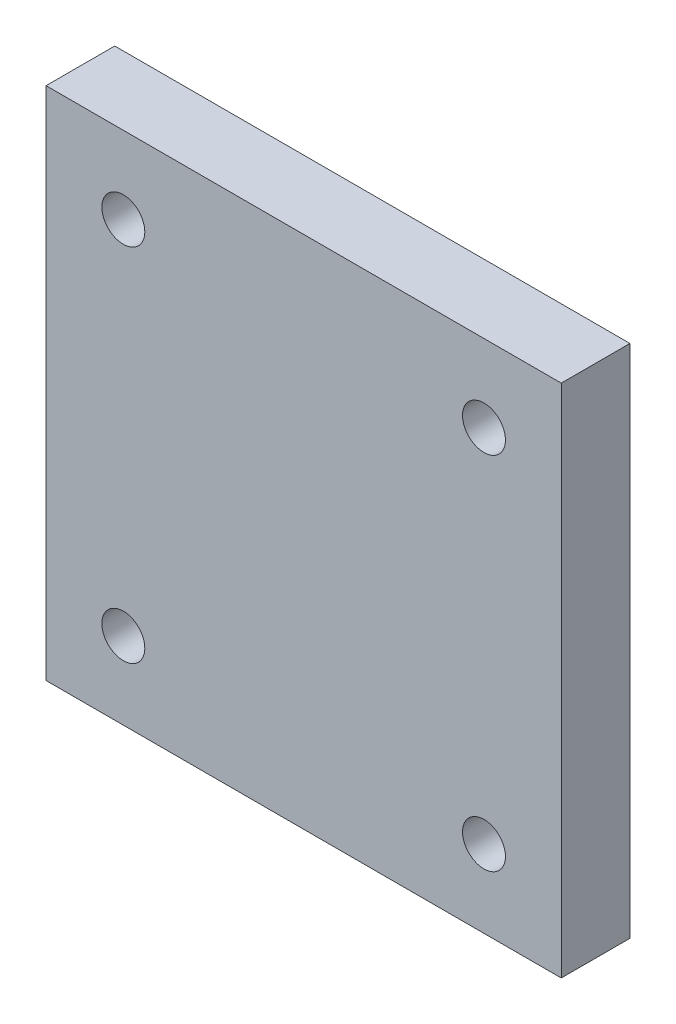
SolidWorks part; units mm, degrees
material "1.0037 (S235JR)"
ref_plane "Płaszczyzna przednia" through (0, 0, 0) normal (0, 0, 1) x (1, 0, 0)
ref_plane "Płaszczyzna górna" through (0, 0, 0) normal (0, 1, 0) x (1, 0, 0)
ref_plane "Płaszczyzna prawa" through (0, 0, 0) normal (1, 0, 0) x (0, 0, -1)
sketch "Szkic1" plane through (0, 0, 0) normal (0, 0, 1) x (1, 0, 0)
  line L0 (-40, 400) -> (-40, 300) construction
  line L1 (-70, 400) -> (-10, 400) construction
  line L3 (-70, 300) -> (-10, 300)
  line L4 (-70, 300) -> (-70, 360)
  line L5 (-70, 360) -> (-10, 360)
  line L6 (-10, 300) -> (-10, 360)
  line L7 (-70, 300) -> (-10, 360) construction
  line L8 (-70, 360) -> (-10, 300) construction
  point P4 (-40, 330)
  dimension "D1" = 60
  dimension "D2" = 60
  dimension "D3" = 100
extrude "Dodanie-wyciągnięcie1" add sketch "Szkic1" along normal blind 8
hole_wizard "Otwór gwintowany M6x1.01" positions "Szkic3" profile "Szkic2" tap size "M6x1.0" standard "Ansi Metric" end condition through all
sketch "Szkic3" plane through (0, 0, 8) normal (0, 0, 1) x (1, 0, 0)
  point P0 (-19, 351)
  point P3 (-61, 351)
  point P6 (-61, 309)
  point P9 (-19, 309)
sketch "Szkic2" plane through (-19, 351, 8) normal (1, 0, 0) x (0, -1, 0)
  line L0 (0, 0) -> (0, 8)
  line L1 (0, 8) -> (2.5, 8)
  line L2 (2.5, 8) -> (2.5, 0)
  line L5 (2.5, 0) -> (0, 0)
  line L11 (0, -6.35) -> (0, 107.95) construction
  dimension "Średnica zewnętrzna gwintu" = 5
  dimension "Głębokość otworu gwintowanego na wylot" = 8
